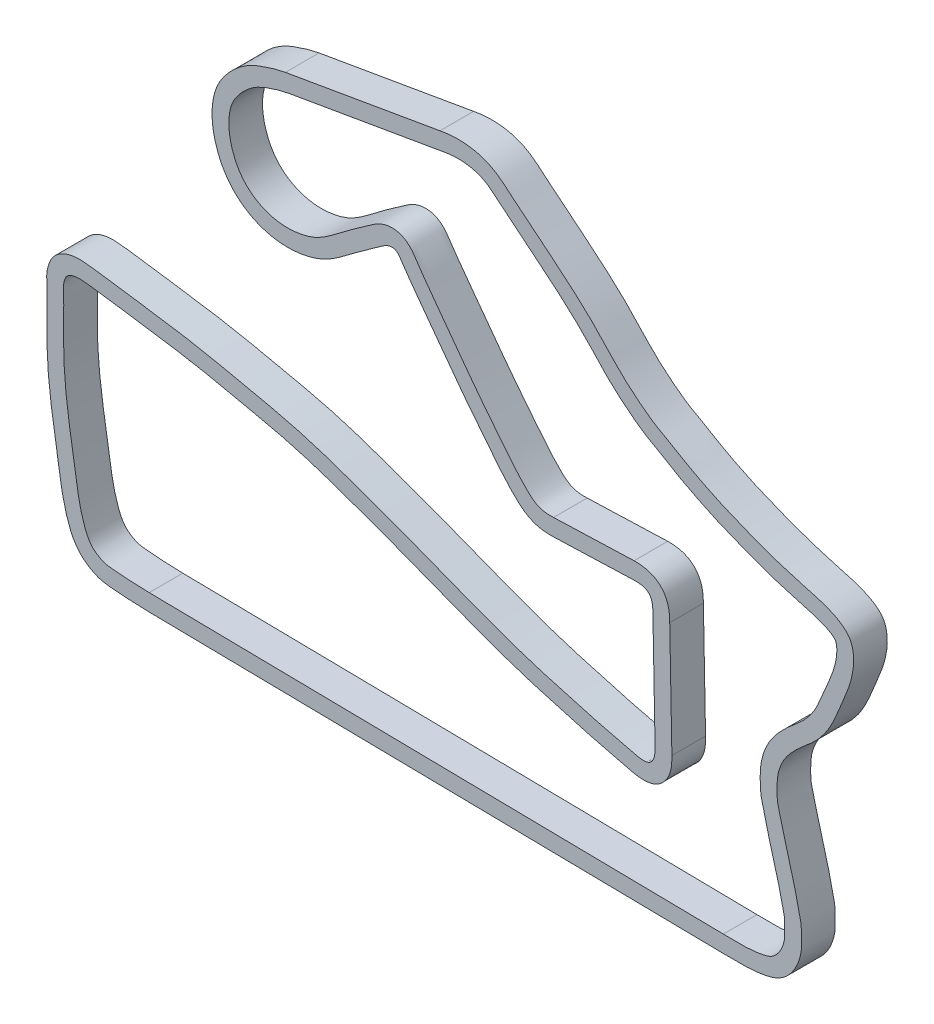
SolidWorks part; units mm, degrees
ref_plane "Front Plane" through (0, 0, 0) normal (0, 0, 1) x (1, 0, 0)
ref_plane "Top Plane" through (0, 0, 0) normal (0, 1, 0) x (1, 0, 0)
ref_plane "Right Plane" through (0, 0, 0) normal (1, 0, 0) x (0, 0, -1)
sketch "Sketch1" plane through (0, 0, 0) normal (0, 0, 1) x (1, 0, 0)
  line L0 (270.1667, 590.5) -> (1350.8333, 590.5) construction
  line L1 (255.8333, 545) -> (1279.1667, 545) construction
  line L6 (510.9481, 0) -> (77.5689, 6.5134)
  line L7 (457.9874, 195.7967) -> (459.6225, 109.7871)
  line L8 (383.4434, 208.2555) -> (444.2084, 210.3603)
  line L9 (180.596, 410.6964) -> (297.281, 430.8472)
  line L10 (511.1389, 12.6986) -> (77.7597, 19.2119)
  line L11 (470.6851, 196.0381) -> (472.3202, 110.0285)
  line L12 (383.0038, 220.9479) -> (443.7687, 223.0527)
  line L13 (182.7573, 398.1817) -> (299.4422, 418.3325)
  spline S0 degree 3 poles (77.5689, 6.5134) (69.0307, 6.6417) (55.964, 7.3696) (40.619, 8.9627) (32.5204, 13.0622) (22.3405, 20.6321) (13.3729, 40.9958) (9.6473, 68.1326) (4.5181, 98.5669) (0.8882, 127.3455) (0.2433, 155.8131) (0.7964, 176.5961) (0.2316, 189.683) (1.818, 195.7723) (3.9694, 201.1113) (8.4451, 206.0517) (15.427, 209.8082) (25.1874, 211.34) (48.2413, 208.2345) (77.1015, 204.0879) (114.2309, 198.4755) (150.5205, 190.5538) (190.2492, 182.1946) (246.071, 163.2951) (294.7616, 144.4879) (340.3552, 126.6466) (368.9495, 116.9946) (398.233, 108.8251) (423.4831, 101.8918) (439.2658, 98.3191) (447.2879, 96.1866) (451.5862, 95.9429) (456.0073, 96.7172) (459.7105, 101.9674) (459.6736, 107.0962) (459.6225, 109.7871) knots 0 0 0 0 0.037554 0.051675 0.063413 0.074522 0.103524 0.151002 0.188457 0.230817 0.270761 0.305807 0.31698 0.324431 0.331626 0.340566 0.351322 0.363771 0.380669 0.446973 0.484528 0.535661 0.600415 0.652007 0.778825 0.816085 0.854228 0.903418 0.941675 0.962299 0.970371 0.975802 0.980082 0.988237 1 1 1 1
  spline S1 degree 3 poles (457.9874, 195.7967) (457.9675, 196.8436) (457.8917, 198.8962) (457.6226, 201.8274) (456.8414, 204.6719) (455.2136, 207.4909) (452.2877, 209.3244) (448.5039, 210.2333) (445.8, 210.4154) (444.2084, 210.3603) knots 0 0 0 0 0.133759 0.259768 0.373044 0.506548 0.662787 0.79459 1 1 1 1
  spline S2 degree 3 poles (383.4434, 208.2555) (380.6542, 208.1589) (375.2808, 208.1637) (368.0453, 209.9571) (362.1701, 212.9838) (357.6843, 216.3901) (348.1132, 225.3474) (338.0133, 237.9923) (324.8053, 254.6028) (312.247, 270.6602) (298.5457, 289.4425) (284.5902, 308.2244) (274.5276, 321.9638) (268.5939, 330.5487) (266.1555, 334.3627) (263.5933, 336.4979) (260.4201, 336.8587) (256.3991, 335.7197) (250.5539, 331.3619) (242.3074, 325.8029) (227.8646, 315.2426) (213.9525, 303.8095) (192.0001, 296.9082) (171.0815, 296.3605) (150.239, 305.1756) (135.8713, 318.9173) (126.9433, 337.2914) (124.0322, 357.5943) (127.9543, 376.1912) (138.0333, 390.5213) (151.2765, 401.5624) (166.6865, 407.312) (176.222, 409.941) (180.596, 410.6964) knots 0 0 0 0 0.018811 0.03554 0.049384 0.06273 0.073096 0.137027 0.170538 0.215176 0.273365 0.32607 0.371729 0.387281 0.395895 0.401988 0.408846 0.416254 0.42951 0.457057 0.483027 0.549403 0.574968 0.635951 0.684859 0.722401 0.766603 0.819027 0.856948 0.890594 0.934458 0.969957 1 1 1 1
  spline S3 degree 3 poles (297.281, 430.8472) (300.0344, 431.3227) (306.6035, 432.3463) (316.9162, 432.2456) (328.4633, 430.1661) (340.2734, 424.936) (354.8488, 411.9093) (375.4042, 395.5753) (397.7312, 377.2183) (418.1623, 357.9542) (432.0293, 341.8468) (447.3254, 328.8219) (459.1844, 319.831) (471.659, 313.5145) (480.1945, 308.2968) (487.5261, 303.8726) (495.8408, 299.726) (506.7624, 294.1955) (531.0878, 283.9348) (559.5951, 273.3622) (587.8327, 266.7986) (600.7994, 260.1661) (607.0555, 253.8348) (609.5616, 245.877) (609.6731, 236.0219) (606.6778, 222.0949) (600.2657, 207.7716) (594.8836, 194.2955) (588.6395, 182.6353) (579.7815, 171.9777) (569.5721, 164.2319) (562.5667, 157.0656) (558.1309, 151.8487) (554.8513, 145.8001) (551.9154, 137.9703) (551.5676, 129.1233) (551.7421, 119.1577) (554.1754, 111.3693) (556.8012, 100.2313) (560.7578, 85.1341) (565.5863, 68.7671) (568.2357, 55.9485) (570.1574, 47.9204) (570.0434, 40.3596) (570.4682, 32.055) (568.4463, 23.7564) (565.0741, 16.3973) (559.9836, 9.5541) (552.489, 3.8807) (543.0931, 1.411) (529.1901, -0.4412) (518.5957, -0.1149) (510.9481, 0) knots 0 0 0 0 0.012275 0.029125 0.045009 0.063546 0.084923 0.130314 0.179056 0.211691 0.253526 0.272049 0.299844 0.318569 0.333312 0.343766 0.356146 0.374083 0.397503 0.472003 0.507371 0.524214 0.535353 0.545336 0.55997 0.578223 0.607408 0.628665 0.641923 0.665345 0.688776 0.697982 0.709328 0.718687 0.728065 0.745775 0.757063 0.771668 0.781284 0.807363 0.840162 0.85611 0.864893 0.876245 0.889154 0.901242 0.913299 0.924502 0.938412 0.953596 0.966529 1 1 1 1
  spline S4 degree 1 poles (77.7597, 19.2119) (472.3202, 110.0285) knots 0 0 1 1 construction
  spline S5 degree 1 poles (470.6851, 196.0381) (443.7687, 223.0527) knots 0 0 1 1 construction
  spline S6 degree 1 poles (383.0038, 220.9479) (182.7573, 398.1817) knots 0 0 1 1 construction
  spline S7 degree 1 poles (299.4422, 418.3325) (511.1389, 12.6986) knots 0 0 1 1 construction
  spline S8 degree 3 poles (77.7597, 19.2119) (76.9002, 19.2248) (75.1965, 19.2584) (71.6679, 19.3589) (67.1449, 19.5442) (62.5114, 19.8054) (58.7815, 20.0571) (55.9767, 20.2665) (53.1919, 20.4959) (50.369, 20.7446) (47.9262, 21.0013) (45.89, 21.3164) (44.5378, 21.636) (43.6597, 21.9139) (42.6953, 22.2751) (41.3824, 22.8766) (39.9492, 23.6764) (38.743, 24.428) (37.6243, 25.1741) (36.3742, 26.1097) (35.3613, 27.0133) (34.6659, 27.7326) (33.6116, 28.9348) (32.0789, 31.1319) (30.1769, 34.9214) (28.478, 39.4098) (26.9751, 44.3059) (25.7144, 49.2704) (24.2676, 56.0989) (23.0866, 63.2098) (21.9602, 70.6134) (20.7824, 78.186) (19.2696, 87.5261) (16.9399, 102.3208) (14.9912, 116.9246) (13.7852, 131.3492) (13.2949, 142.2576) (13.1547, 151.4466) (13.1719, 158.8154) (13.231, 164.429) (13.291, 170.1423) (13.3063, 174.9872) (13.2739, 178.9229) (13.2313, 181.3937) (13.1776, 183.412) (13.1258, 185.2255) (13.1131, 186.7356) (13.1642, 187.9278) (13.2306, 188.6552) (13.3197, 189.2486) (13.4714, 189.9818) (13.6817, 190.7869) (13.962, 191.6994) (14.2773, 192.6067) (14.5507, 193.2859) (14.7966, 193.7984) (14.9629, 194.0883) (15.166, 194.3862) (15.5322, 194.8399) (16.1484, 195.4501) (17.3941, 196.3769) (18.9757, 197.1479) (20.8612, 197.6811) (23.0352, 198.0638) (26.0819, 198.1984) (29.8595, 197.8768) (33.325, 197.4264) (37.0957, 196.9081) (41.7604, 196.2669) (47.3703, 195.4844) (54.8366, 194.4322) (64.1629, 193.0974) (75.3436, 191.4654) (86.5465, 189.8099) (97.6487, 188.1141) (108.5904, 186.2815) (123.1024, 183.5114) (137.7864, 180.3498) (152.6316, 177.1701) (167.286, 173.9843) (181.6842, 170.5805) (195.697, 166.6123) (209.744, 162.1923) (227.4074, 156.0561) (248.617, 148.3739) (269.748, 140.4457) (287.3384, 133.6888) (301.4165, 128.225) (311.9625, 124.1113) (322.5862, 119.9682) (333.359, 115.8784) (344.2915, 111.9561) (355.2758, 108.2587) (366.3413, 104.7725) (377.3989, 101.504) (386.5874, 98.9025) (393.9176, 96.8637) (399.3941, 95.3487) (404.9006, 93.8328) (410.4404, 92.3312) (416.0173, 90.8567) (421.6265, 89.4228) (426.3535, 88.2738) (430.0558, 87.3973) (432.7986, 86.7475) (435.497, 86.0999) (437.7345, 85.549) (439.4591, 85.1107) (440.9228, 84.7356) (442.585, 84.3358) (444.4457, 83.9466) (446.5225, 83.6109) (448.7886, 83.386) (450.8269, 83.3354) (452.5256, 83.4052) (453.8591, 83.5187) (455.4155, 83.7396) (457.1691, 84.1272) (459.1109, 84.7468) (461.2652, 85.739) (463.1608, 86.9391) (465.3491, 88.7048) (467.4812, 91.0877) (469.3023, 93.9765) (470.5946, 96.847) (471.4567, 99.6432) (471.9664, 102.2312) (472.2313, 104.5855) (472.3352, 106.6888) (472.3452, 108.2162) (472.3334, 109.3095) (472.3248, 109.7828) (472.3202, 110.0285) knots 0 0 0 0 0.003906 0.007812 0.015625 0.023438 0.027344 0.03125 0.035156 0.039062 0.042969 0.046875 0.050781 0.052734 0.054688 0.058594 0.0625 0.064453 0.066406 0.070312 0.074219 0.076172 0.078125 0.085938 0.09375 0.101562 0.109375 0.117188 0.125 0.140625 0.148438 0.15625 0.171875 0.1875 0.21875 0.234375 0.25 0.265625 0.273438 0.28125 0.289062 0.296875 0.300781 0.304688 0.306641 0.308594 0.3125 0.314453 0.316406 0.318359 0.320312 0.322266 0.324219 0.326172 0.328125 0.330078 0.332031 0.333984 0.335938 0.339844 0.34375 0.351562 0.355469 0.359375 0.367188 0.375 0.378906 0.382812 0.390625 0.398438 0.40625 0.421875 0.4375 0.453125 0.46875 0.484375 0.5 0.53125 0.546875 0.5625 0.59375 0.609375 0.625 0.65625 0.6875 0.71875 0.75 0.765625 0.78125 0.796875 0.8125 0.828125 0.84375 0.859375 0.875 0.890625 0.898438 0.90625 0.914062 0.921875 0.929688 0.9375 0.945312 0.949219 0.953125 0.957031 0.960938 0.962891 0.964844 0.966797 0.96875 0.970703 0.972656 0.974609 0.975586 0.976562 0.977539 0.978516 0.979492 0.980469 0.981445 0.982422 0.984375 0.986328 0.988281 0.990234 0.992188 0.994141 0.996094 0.998047 0.999023 1 1 1 1
  spline S9 degree 3 poles (470.6851, 196.0381) (470.663, 197.2015) (470.603, 198.8625) (470.421, 201.4076) (470.1267, 203.7869) (469.5441, 206.491) (468.5934, 209.3352) (467.3741, 211.8512) (466.012, 213.935) (464.7556, 215.5116) (463.2716, 217.0087) (461.2628, 218.6554) (458.6998, 220.2284) (455.6136, 221.5139) (453.2973, 222.1403) (451.66, 222.4724) (450.1736, 222.7213) (447.537, 223.0407) (445.2755, 223.1049) (443.7687, 223.0527) knots 0 0 0 0 0.125 0.1875 0.25 0.3125 0.375 0.4375 0.46875 0.5 0.53125 0.5625 0.625 0.6875 0.75 0.78125 0.8125 0.875 1 1 1 1
  spline S10 degree 3 poles (383.0038, 220.9479) (382.5026, 220.9305) (381.4783, 220.9029) (379.6019, 220.8956) (377.4791, 220.9903) (375.3871, 221.2841) (373.3453, 221.8024) (371.5011, 222.5065) (368.9704, 223.8158) (366.4253, 225.6663) (363.6622, 228.1804) (360.6589, 231.1388) (357.0435, 235.0055) (352.7459, 240.0024) (348.4744, 245.2482) (344.1245, 250.7169) (339.7709, 256.1885) (335.446, 261.6516) (329.7158, 268.9381) (322.7111, 278.0166) (315.8472, 287.2863) (310.3248, 294.8033) (306.1494, 300.4736) (301.975, 306.1167) (297.8094, 311.7446) (294.3486, 316.4293) (291.5982, 320.1673) (289.5502, 322.9647) (287.5193, 325.7585) (285.5076, 328.5513) (283.5207, 331.3419) (281.8792, 333.6768) (280.6099, 335.5103) (279.8376, 336.6435) (279.2319, 337.5458) (278.788, 338.2138) (278.3389, 338.9009) (277.5128, 340.1454) (276.3446, 341.7726) (274.6861, 343.6262) (273.0898, 345.1237) (271.3509, 346.4081) (269.6697, 347.371) (267.7385, 348.2615) (265.3824, 348.9745) (262.7646, 349.3586) (260.3628, 349.4036) (257.398, 349.13) (254.1044, 348.2984) (250.843, 346.8896) (248.252, 345.3799) (246.5792, 344.232) (245.4735, 343.4381) (244.776, 342.9321) (244.1127, 342.456) (243.2059, 341.8103) (242.0619, 341.0047) (240.6638, 340.0303) (238.7705, 338.7185) (236.3524, 337.0479) (233.3715, 334.9545) (230.4234, 332.8321) (227.4984, 330.6806) (223.6016, 327.7509) (218.9387, 324.1519) (213.6326, 320.2165) (208.5303, 316.8456) (204.4289, 314.64) (201.1836, 313.2686) (197.7313, 312.0576) (193.1049, 310.87) (185.4994, 309.7238) (177.8963, 309.8034) (170.6785, 311.1554) (165.4365, 312.8256) (160.4719, 315.1207) (155.9139, 317.9849) (151.7814, 321.4222) (148.1644, 325.3485) (145.1367, 329.7008) (141.7191, 336.2398) (138.6886, 345.51) (137.6902, 354.8391) (138.2133, 362.1931) (139.0998, 366.4771) (140.1428, 369.6224) (141.3778, 372.5059) (143.5013, 376.113) (146.3923, 379.7455) (149.0077, 382.5293) (151.7269, 385.1205) (154.609, 387.4283) (157.6176, 389.4082) (160.6661, 391.1401) (164.9537, 393.0719) (169.8744, 394.7915) (174.0313, 396.0867) (177.033, 396.9336) (179.4684, 397.5293) (181.3693, 397.9296) (182.2912, 398.1012) (182.7573, 398.1817) knots 0 0 0 0 0.003906 0.007812 0.015625 0.023438 0.03125 0.039062 0.046875 0.0625 0.070312 0.078125 0.09375 0.109375 0.125 0.140625 0.15625 0.171875 0.1875 0.21875 0.25 0.265625 0.28125 0.296875 0.3125 0.328125 0.335938 0.34375 0.351562 0.359375 0.367188 0.375 0.378906 0.382812 0.384766 0.386719 0.388672 0.390625 0.394531 0.396484 0.398438 0.400391 0.401367 0.402344 0.404297 0.40625 0.408203 0.410156 0.414062 0.417969 0.421875 0.425781 0.427734 0.429688 0.431641 0.433594 0.4375 0.441406 0.445312 0.453125 0.460938 0.46875 0.476562 0.484375 0.5 0.515625 0.53125 0.546875 0.554688 0.5625 0.578125 0.59375 0.625 0.640625 0.65625 0.671875 0.6875 0.703125 0.71875 0.734375 0.75 0.78125 0.8125 0.828125 0.84375 0.851562 0.859375 0.875 0.890625 0.898438 0.90625 0.921875 0.929688 0.9375 0.953125 0.96875 0.976562 0.984375 0.992188 0.996094 1 1 1 1
  spline S11 degree 3 poles (299.4422, 418.3325) (299.8531, 418.4034) (300.6831, 418.5445) (302.2812, 418.803) (304.9852, 419.1962) (308.4638, 419.52) (312.7406, 419.5392) (317.0757, 419.2009) (321.2213, 418.5241) (325.0806, 417.4958) (328.1542, 416.303) (330.4823, 415.1622) (332.1446, 414.2229) (333.7327, 413.1924) (335.4193, 411.9675) (337.1775, 410.5786) (339.0268, 409.0333) (340.9677, 407.3605) (343.7421, 404.9603) (347.2468, 401.9944) (351.4439, 398.5144) (357.0378, 393.9481) (363.9946, 388.353) (372.2255, 381.7044) (380.3373, 375.0148) (388.2743, 368.248) (395.987, 361.3578) (403.428, 354.3028) (410.431, 347.0699) (417.6656, 339.1806) (424.1624, 332.4148) (429.8707, 327.083) (434.2045, 323.3295) (438.5207, 319.7763) (442.9757, 316.2546) (447.6765, 312.7845) (451.7964, 310.0132) (455.2819, 307.8814) (457.8527, 306.41) (460.33, 305.0482) (462.7044, 303.7655) (464.9665, 302.5354) (467.7801, 300.9536) (470.6833, 299.2231) (473.6852, 297.4011) (476.0002, 295.9949) (478.4305, 294.5443) (481.0176, 293.0627) (483.6468, 291.6517) (487.0215, 289.9228) (490.9536, 287.959) (495.8177, 285.5171) (500.9003, 283.0692) (506.0408, 280.7576) (511.1361, 278.582) (516.1738, 276.5049) (526.2497, 272.4306) (538.2006, 267.8836) (552.1517, 263.1909) (561.0029, 260.5049) (568.185, 258.5452) (575.0149, 256.7396) (582.8433, 254.4755) (589.7215, 251.6388) (593.1129, 249.4729) (594.6541, 248.1862) (595.2789, 247.5244) (595.5904, 247.1194) (595.7246, 246.9125) (595.8263, 246.7256) (596.0291, 246.273) (596.3092, 245.4196) (596.7045, 243.458) (596.8919, 240.6867) (596.6175, 236.7324) (595.9072, 232.6163) (594.802, 228.3876) (593.3385, 224.0436) (591.5623, 219.5009) (589.8931, 215.5369) (588.4945, 212.2453) (587.0701, 208.8491) (585.3947, 204.7864) (583.4176, 200.2153) (581.3833, 195.9879) (579.2292, 192.1389) (576.8646, 188.6364) (574.1441, 185.2479) (571.6506, 182.6032) (569.524, 180.5953) (567.1594, 178.4952) (564.507, 176.2638) (561.6405, 173.8044) (559.4075, 171.8149) (557.1377, 169.6549) (554.9919, 167.466) (552.9618, 165.2806) (550.8602, 162.8769) (548.7431, 160.2028) (546.6668, 157.1605) (544.8908, 154.059) (543.3808, 150.978) (542.0337, 147.7757) (540.8448, 144.2853) (539.9377, 140.527) (539.3986, 136.9801) (539.1013, 133.602) (538.9947, 130.958) (538.9584, 128.9364) (538.948, 127.4954) (538.949, 126.0113) (538.9812, 123.9225) (539.0841, 121.6852) (539.3125, 119.3118) (539.6574, 116.8141) (540.2408, 113.953) (541.018, 110.9186) (541.7678, 108.2354) (542.3776, 105.9624) (542.9796, 103.5183) (543.6039, 100.9179) (544.2601, 98.2455) (545.1467, 94.7163) (546.2893, 90.3088) (547.7052, 85.0434) (549.1656, 79.8021) (550.6098, 74.6807) (551.9957, 69.6537) (553.2892, 64.7024) (554.2378, 60.6794) (554.9842, 57.2911) (555.5541, 54.6797) (556.0496, 52.4387) (556.466, 50.6219) (556.8254, 49.0399) (557.0881, 47.7131) (557.2237, 46.7578) (557.3238, 45.7163) (557.3964, 44.0382) (557.4104, 41.9509) (557.4381, 39.9716) (557.4815, 38.1264) (557.5243, 36.0988) (557.4883, 34.0856) (557.3571, 32.6049) (557.0737, 30.9978) (556.6348, 29.2952) (556.0376, 27.4971) (555.3394, 25.7658) (554.5493, 24.1251) (553.3688, 22.0496) (552.0423, 20.2224) (550.6206, 18.7025) (549.4764, 17.6797) (548.2846, 16.8005) (547.0944, 16.0912) (545.8839, 15.5296) (543.8324, 14.7923) (541.2132, 14.1619) (538.2225, 13.6275) (535.2414, 13.1951) (531.4272, 12.8195) (526.6612, 12.5968) (521.6917, 12.5452) (517.3845, 12.5947) (513.8512, 12.6545) (512.0392, 12.685) (511.1389, 12.6986) knots 0 0 0 0 0.001953 0.003906 0.007812 0.015625 0.023438 0.03125 0.039062 0.046875 0.054688 0.058594 0.0625 0.066406 0.070312 0.074219 0.078125 0.082031 0.085938 0.09375 0.101562 0.109375 0.125 0.140625 0.15625 0.171875 0.1875 0.203125 0.21875 0.234375 0.25 0.257812 0.265625 0.273438 0.28125 0.289062 0.296875 0.300781 0.304688 0.308594 0.3125 0.316406 0.320312 0.328125 0.332031 0.335938 0.339844 0.34375 0.347656 0.351562 0.359375 0.367188 0.375 0.382812 0.390625 0.398438 0.40625 0.4375 0.453125 0.46875 0.476562 0.484375 0.5 0.515625 0.523438 0.527344 0.53125 0.533203 0.535156 0.537109 0.539062 0.542969 0.546875 0.554688 0.5625 0.570312 0.578125 0.585938 0.59375 0.601562 0.605469 0.609375 0.617188 0.625 0.632812 0.640625 0.648438 0.65625 0.664062 0.667969 0.671875 0.679688 0.683594 0.6875 0.691406 0.695312 0.699219 0.703125 0.707031 0.710938 0.714844 0.71875 0.722656 0.726562 0.730469 0.734375 0.738281 0.742188 0.744141 0.746094 0.748047 0.75 0.753906 0.755859 0.757812 0.761719 0.765625 0.769531 0.773438 0.777344 0.78125 0.785156 0.789062 0.796875 0.804688 0.8125 0.820312 0.828125 0.835938 0.84375 0.847656 0.851562 0.855469 0.857422 0.859375 0.863281 0.865234 0.867188 0.871094 0.875 0.876953 0.878906 0.882812 0.886719 0.890625 0.894531 0.898438 0.902344 0.90625 0.910156 0.914062 0.921875 0.925781 0.929688 0.933594 0.9375 0.941406 0.945312 0.953125 0.957031 0.960938 0.96875 0.976562 0.984375 0.992188 0.996094 1 1 1 1
  dimension "D1" = 12.7
extrude "Boss-Extrude1" add sketch "Sketch1" along normal blind 25.4
scale "Scale1" scale about origin uniform scaling yes scale factor 1.5
